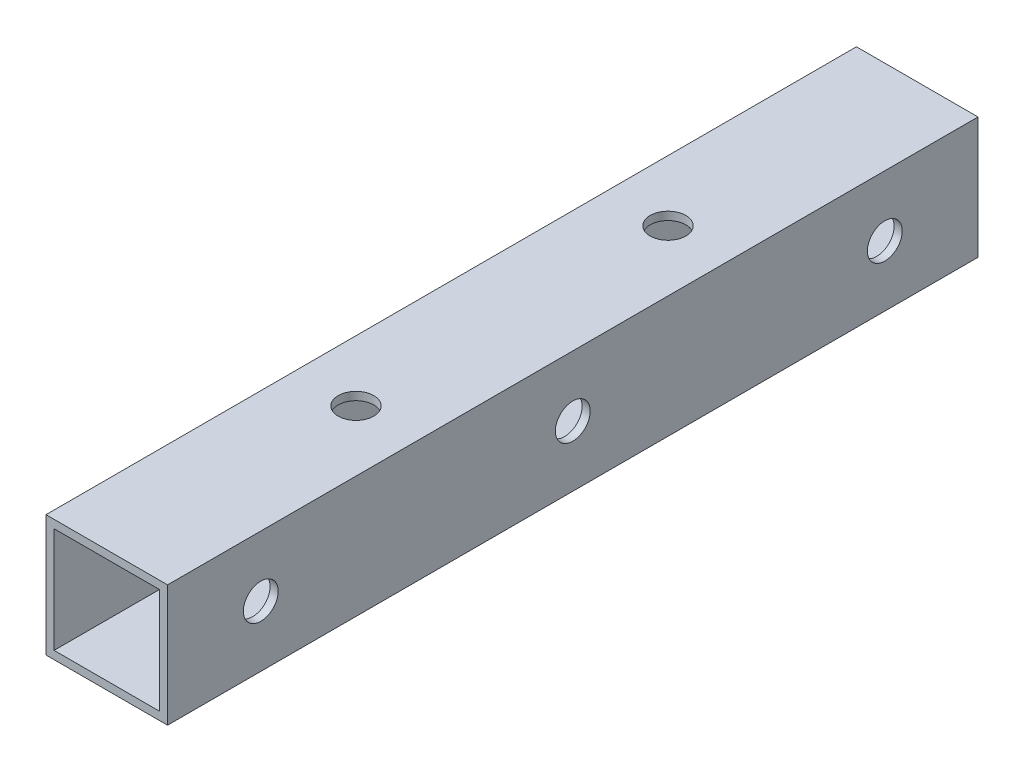
SolidWorks part; units mm, degrees
ref_plane "前视基准面" through (0, 0, 0) normal (0, 0, 1) x (1, 0, 0)
ref_plane "上视基准面" through (0, 0, 0) normal (0, 1, 0) x (1, 0, 0)
ref_plane "右视基准面" through (0, 0, 0) normal (1, 0, 0) x (0, 0, -1)
other "Configuration Table"
sketch "草图1" plane through (0, 0, 0) normal (0, 0, 1) x (1, 0, 0)
  line L1 (-7.5, 7.5) -> (7.5, 7.5)
  line L2 (-7.5, 7.5) -> (-7.5, -7.5)
  line L3 (-7.5, -7.5) -> (7.5, -7.5)
  line L4 (7.5, 7.5) -> (7.5, -7.5)
  line L5 (-7.5, 7.5) -> (7.5, -7.5) construction
  line L6 (-7.5, -7.5) -> (7.5, 7.5) construction
  line L7 (-6.5, 6.5) -> (6.5, 6.5)
  line L8 (-6.5, 6.5) -> (-6.5, -6.5)
  line L9 (-6.5, -6.5) -> (6.5, -6.5)
  line L10 (6.5, 6.5) -> (6.5, -6.5)
  line L11 (-6.5, 6.5) -> (6.5, -6.5) construction
  line L12 (-6.5, -6.5) -> (6.5, 6.5) construction
  point P0 (0, 0)
  point P5 (0, 0)
  dimension "D1" = 15
  dimension "D2" = 15
  dimension "D3" = 1
  dimension "D4" = 1
extrude "凸台-拉伸1" add sketch "草图1" along normal blind 100
sketch "草图2" plane through (7.5, 0, 0) normal (1, 0, 0) x (0, 0, -1)
  line L0 (-100, 0) -> (0, 0) construction
  line L1 (-100, -7.5) -> (-100, 7.5) construction
  line L2 (-50, 7.5) -> (-50, -7.5) construction
  line L3 (-100, 7.5) -> (0, 7.5) construction
  line L4 (-100, -7.5) -> (0, -7.5) construction
  circle A0 centre (-50, 0) radius 2.15
  circle A1 centre (-88.5, 0) radius 2.15
  circle A2 centre (-11.5, 0) radius 2.15
  dimension "D1" = 4.3
  dimension "D2" = 77
  dimension "D3" = 4.3
extrude "切除-拉伸1" cut sketch "草图2" against normal blind 366
sketch "草图3" plane through (0, 7.5, 0) normal (0, 1, 0) x (1, 0, 0)
  line L0 (0, 0) -> (0, -100) construction
  line L1 (7.5, -100) -> (-7.5, -100) construction
  line L2 (-7.5, -50) -> (7.5, -50) construction
  line L3 (-7.5, -100) -> (-7.5, 0) construction
  line L4 (7.5, -100) -> (7.5, 0) construction
  circle A0 centre (0, -30.75) radius 2.2
  circle A1 centre (0, -69.25) radius 2.2
  dimension "D1" = 38.5
  dimension "D2" = 4.4
extrude "切除-拉伸2" cut sketch "草图3" against normal blind 55
